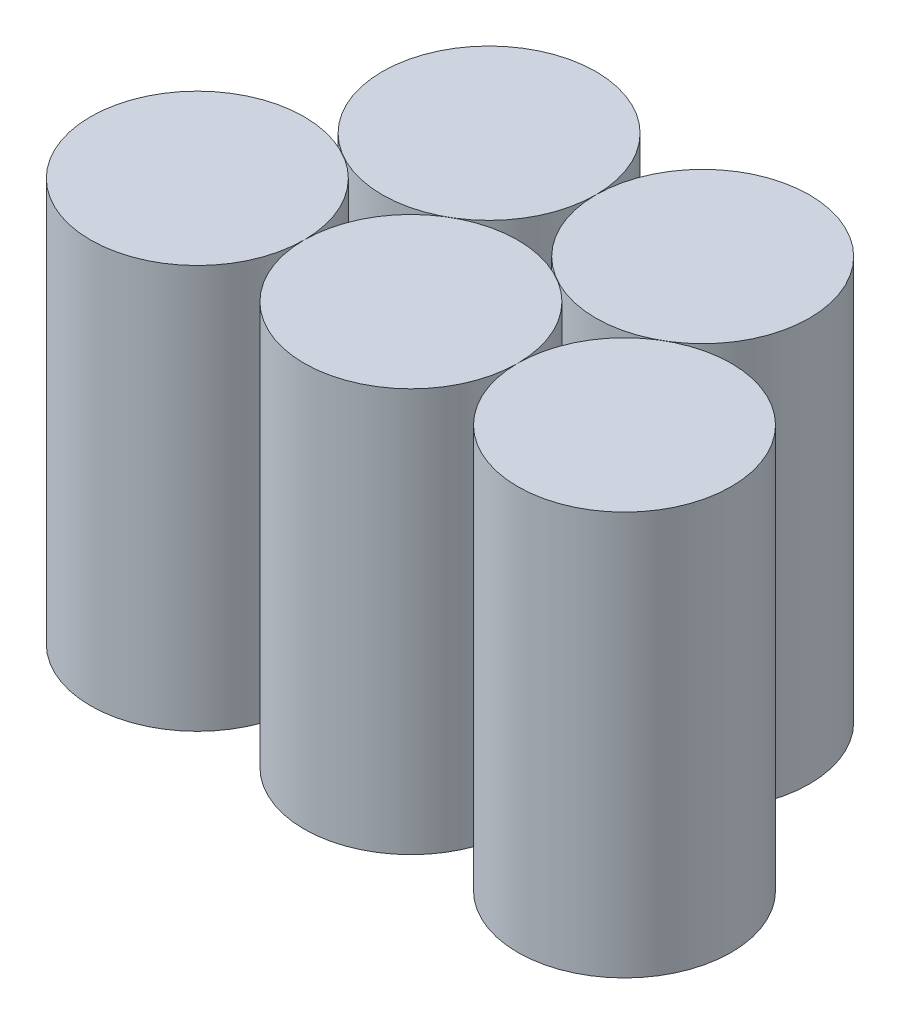
SolidWorks part; units mm, degrees
ref_plane "Front Plane" through (0, 0, 0) normal (0, 0, 1) x (1, 0, 0)
ref_plane "Top Plane" through (0, 0, 0) normal (0, 1, 0) x (1, 0, 0)
ref_plane "Right Plane" through (0, 0, 0) normal (1, 0, 0) x (0, 0, -1)
sketch "Sketch1" plane through (0, 0, 0) normal (0, 1, 0) x (1, 0, 0)
  circle A0 centre (0, -11.43) radius 11.43
  circle A1 centre (22.86, -11.43) radius 11.43
  circle A2 centre (-22.86, -11.43) radius 11.43
  circle A3 centre (-11.43, 8.3673) radius 11.43
  circle A4 centre (11.43, 8.3673) radius 11.43
  point P11 (0, 0)
  point P12 (0, 0)
  point P13 (0, 0)
  dimension "D1" = 22.86
extrude "Boss-Extrude1" add sketch "Sketch1" along normal blind 43.18 contours A2 | A3 | A0 | A4 | A1
